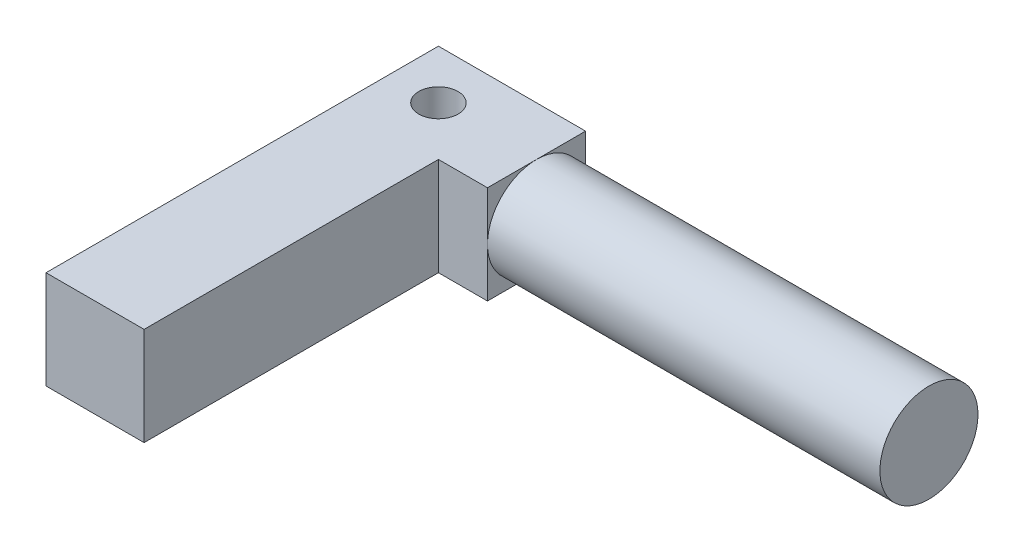
SolidWorks part; units mm, degrees
ref_plane "Front Plane" through (0, 0, 0) normal (0, 0, 1) x (1, 0, 0)
ref_plane "Top Plane" through (0, 0, 0) normal (0, 1, 0) x (1, 0, 0)
ref_plane "Right Plane" through (0, 0, 0) normal (1, 0, 0) x (0, 0, -1)
sketch "Sketch1" plane through (0, 0, 0) normal (0, 1, 0) x (1, 0, 0)
  line L1 (-25, 25) -> (25, 25)
  line L2 (-25, 25) -> (-25, -175)
  line L3 (-25, -175) -> (25, -175)
  line L4 (25, -25) -> (25, -175)
  line L5 (25, 25) -> (50, 25)
  line L7 (25, -25) -> (50, -25)
  line L8 (50, 25) -> (50, -25)
  circle A0 centre (0, 0) radius 10
  dimension "D1" = 20
  dimension "D2" = 25
  dimension "D3" = 25
  dimension "D4" = 200
  dimension "D5" = 25
  dimension "D6" = 50
  dimension "D7" = 25
extrude "Boss-Extrude2" add sketch "Sketch1" along normal blind 50 contours L4 L3 L2 L1 L5 L8 L7
sketch "Sketch2" plane through (0, 0, 0) normal (0, -1, 0) x (1, 0, 0)
  circle A0 centre (0, 0) radius 10
  dimension "D1" = 20
extrude "Cut-Extrude1" cut sketch "Sketch2" against normal through all
sketch "Sketch3" plane through (50, 0, 0) normal (1, 0, 0) x (0, 0, -1)
  line L0 (0, 50) -> (0, 0) construction
  line L1 (25, 50) -> (-25, 50) construction
  circle A0 centre (0, 25) radius 25
extrude "Boss-Extrude3" add sketch "Sketch3" along normal blind 200
